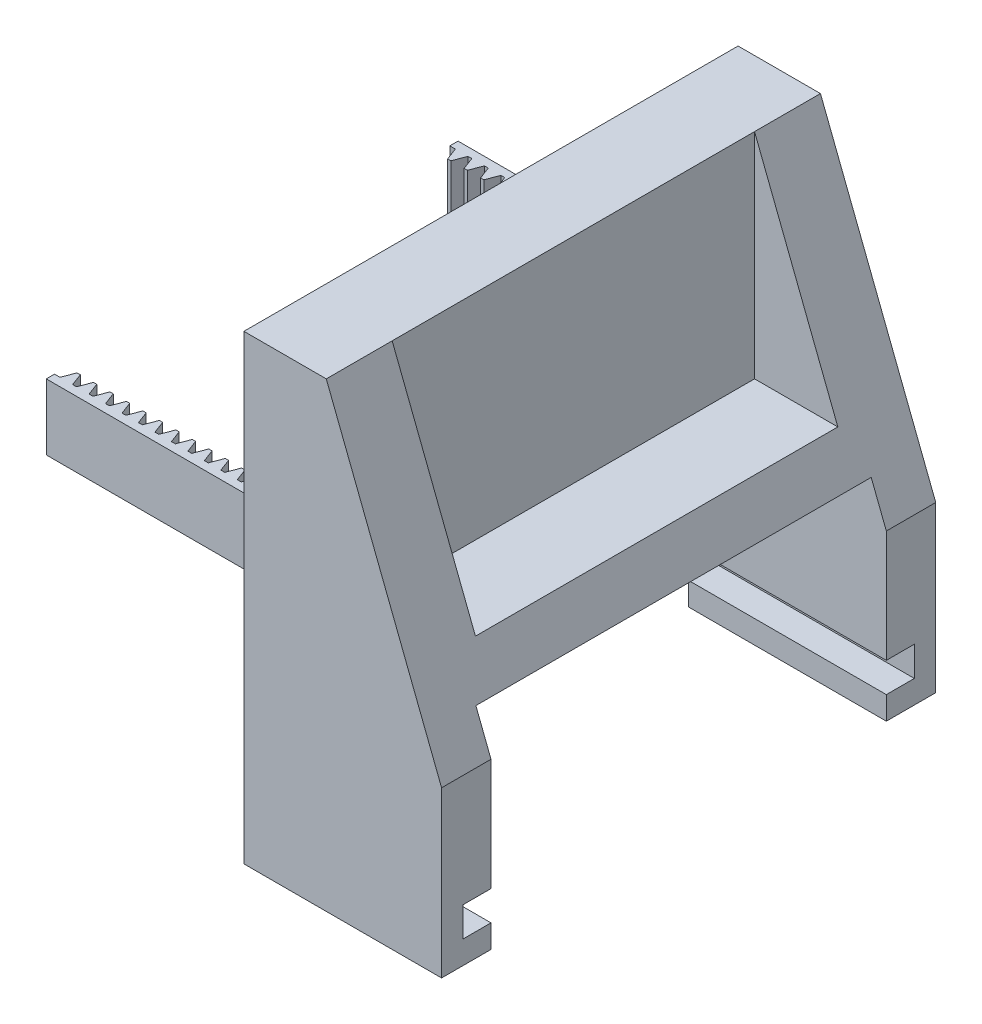
SolidWorks part; units mm, degrees
ref_plane "Front Plane" through (0, 0, 0) normal (0, 0, 1) x (1, 0, 0)
ref_plane "Top Plane" through (0, 0, 0) normal (0, 1, 0) x (1, 0, 0)
ref_plane "Right Plane" through (0, 0, 0) normal (1, 0, 0) x (0, 0, -1)
sketch "Sketch1" plane through (0, 0, 0) normal (0, 0, 1) x (1, 0, 0)
  line L0 (0, 0) -> (0, -28)
  line L1 (0, -28) -> (12, -28)
  line L2 (12, -28) -> (12, -18)
  line L3 (12, -18) -> (5, 0)
  line L4 (5, 0) -> (0, 0)
  dimension "D1" = 28
  dimension "D2" = 12
  dimension "D3" = 10
  dimension "D4" = 5
extrude "Boss-Extrude1" add sketch "Sketch1" against normal blind 30
sketch "Sketch4" plane through (0, 0, 0) normal (-1, 0, 0) x (0, 0, 1)
  line L0 (-30, 0) -> (-30, -28) construction
  line L1 (-27, -15.6386) -> (-3, -15.6386)
  line L2 (-27, -15.6386) -> (-27, -29.6386)
  line L3 (-27, -29.6386) -> (-3, -29.6386)
  line L4 (-3, -15.6386) -> (-3, -29.6386)
  point P4 (-27, -22.6386)
  dimension "D1" = 24
  dimension "D2" = 14
  dimension "D3" = 3
extrude "Cut-Extrude2" cut sketch "Sketch4" against normal blind 25 contours L2 L1 L4 L3
sketch "Sketch5" plane through (0, 0, 0) normal (-1, 0, 0) x (0, 0, 1)
  line L0 (-3, -15.6386) -> (-3, -28) construction
  line L1 (-3, -24.8) -> (-1.3, -24.8)
  line L2 (-3, -24.8) -> (-3, -26.6)
  line L3 (-3, -26.6) -> (-1.3, -26.6)
  line L4 (-1.3, -24.8) -> (-1.3, -26.6)
  line L5 (-3, -28) -> (0, -28) construction
  dimension "D1" = 1.8
  dimension "D2" = 1.7
  dimension "D3" = 1.4
extrude "Cut-Extrude3" cut sketch "Sketch5" against normal blind 15
ref_plane "Plane1" through (0, 0, -15) normal (0, 0, 1) x (1, 0, 0)
mirror "Mirror1" about plane through (0, 0, -15) normal (0, 0, 1) of "Cut-Extrude3"
sketch "Sketch6" plane through (0, 0, -15) normal (0, 0, 1) x (1, 0, 0)
  line L0 (5, 0) -> (5, -13)
  line L1 (5, -13) -> (10.0556, -13)
  line L2 (12, -18) -> (5, 0) construction
  line L3 (10.0556, -13) -> (5, 0)
  dimension "D1" = 13
extrude "Cut-Extrude4" cut sketch "Sketch6" against normal mid plane 22
ref_plane "Plane2" through (0, -15, 0) normal (0, 1, 0) x (1, 0, 0)
sketch "Sketch7" plane through (0, -15, 0) normal (0, 1, 0) x (1, 0, 0)
  line L0 (0, 27.5) -> (-14.5, 27.5)
  line L1 (0, 30) -> (0, 0) construction
  line L2 (-14.5, 27.5) -> (-14.5, 27)
  line L3 (0, 27.5) -> (0, 27)
  line L4 (0, 27) -> (-0.4, 27)
  line L5 (-0.8812, 26.251) -> (-1.1644, 27)
  line L6 (-0.4, 27) -> (-0.6812, 26.251)
  line L7 (-0.6812, 26.251) -> (-0.8812, 26.251)
  line L8 (-1.8812, 26.251) -> (-2.1644, 27)
  line L9 (-1.6812, 26.251) -> (-1.8812, 26.251)
  line L10 (-1.4, 27) -> (-1.6812, 26.251)
  line L11 (-2.8812, 26.251) -> (-3.1644, 27)
  line L12 (-2.6812, 26.251) -> (-2.8812, 26.251)
  line L13 (-2.4, 27) -> (-2.6812, 26.251)
  line L14 (-3.8812, 26.251) -> (-4.1644, 27)
  line L15 (-3.6812, 26.251) -> (-3.8812, 26.251)
  line L16 (-3.4, 27) -> (-3.6812, 26.251)
  line L17 (-4.8812, 26.251) -> (-5.1644, 27)
  line L18 (-4.6812, 26.251) -> (-4.8812, 26.251)
  line L19 (-4.4, 27) -> (-4.6812, 26.251)
  line L20 (-5.8812, 26.251) -> (-6.1644, 27)
  line L21 (-5.6812, 26.251) -> (-5.8812, 26.251)
  line L22 (-5.4, 27) -> (-5.6812, 26.251)
  line L23 (-6.8812, 26.251) -> (-7.1644, 27)
  line L24 (-6.6812, 26.251) -> (-6.8812, 26.251)
  line L25 (-6.4, 27) -> (-6.6812, 26.251)
  line L26 (-7.8812, 26.251) -> (-8.1644, 27)
  line L27 (-7.6812, 26.251) -> (-7.8812, 26.251)
  line L28 (-7.4, 27) -> (-7.6812, 26.251)
  line L29 (-8.8812, 26.251) -> (-9.1644, 27)
  line L30 (-8.6812, 26.251) -> (-8.8812, 26.251)
  line L31 (-8.4, 27) -> (-8.6812, 26.251)
  line L32 (-9.8812, 26.251) -> (-10.1644, 27)
  line L33 (-9.6812, 26.251) -> (-9.8812, 26.251)
  line L34 (-9.4, 27) -> (-9.6812, 26.251)
  line L35 (-10.8812, 26.251) -> (-11.1644, 27)
  line L36 (-10.6812, 26.251) -> (-10.8812, 26.251)
  line L37 (-10.4, 27) -> (-10.6812, 26.251)
  line L38 (-11.8812, 26.251) -> (-12.1644, 27)
  line L39 (-11.6812, 26.251) -> (-11.8812, 26.251)
  line L40 (-11.4, 27) -> (-11.6812, 26.251)
  line L41 (-12.8812, 26.251) -> (-13.1644, 27)
  line L42 (-12.6812, 26.251) -> (-12.8812, 26.251)
  line L43 (-12.4, 27) -> (-12.6812, 26.251)
  line L44 (-13.8812, 26.251) -> (-14.1644, 27)
  line L45 (-13.6812, 26.251) -> (-13.8812, 26.251)
  line L46 (-13.4, 27) -> (-13.6812, 26.251)
  line L47 (-0.8812, 26.251) -> (-1.8812, 26.251) construction
  line L48 (-1.1644, 27) -> (-1.4, 27)
  line L49 (-2.1644, 27) -> (-2.4, 27)
  line L50 (-3.1644, 27) -> (-3.4, 27)
  line L51 (-4.1644, 27) -> (-4.4, 27)
  line L52 (-5.1644, 27) -> (-5.4, 27)
  line L53 (-6.1644, 27) -> (-6.4, 27)
  line L54 (-7.1644, 27) -> (-7.4, 27)
  line L55 (-8.1644, 27) -> (-8.4, 27)
  line L56 (-9.1644, 27) -> (-9.4, 27)
  line L57 (-10.1644, 27) -> (-10.4, 27)
  line L58 (-11.1644, 27) -> (-11.4, 27)
  line L59 (-12.1644, 27) -> (-12.4, 27)
  line L60 (-13.1644, 27) -> (-13.4, 27)
  line L61 (-14.1644, 27) -> (-14.5, 27)
  line L62 (-6.6, 15) -> (6.6, 15) construction
  dimension "D1" = 0.8
  dimension "D4" = 0.2
  dimension "D2" = 14.5
  dimension "D3" = 0.5
  dimension "D5" = 1
  dimension "D6" = 0.4
  dimension "D7" = 12.5
extrude "Boss-Extrude2" add sketch "Sketch7" along normal blind 4
mirror "Mirror2" about plane through (0, 0, -15) normal (0, 0, 1) of "Boss-Extrude2"
